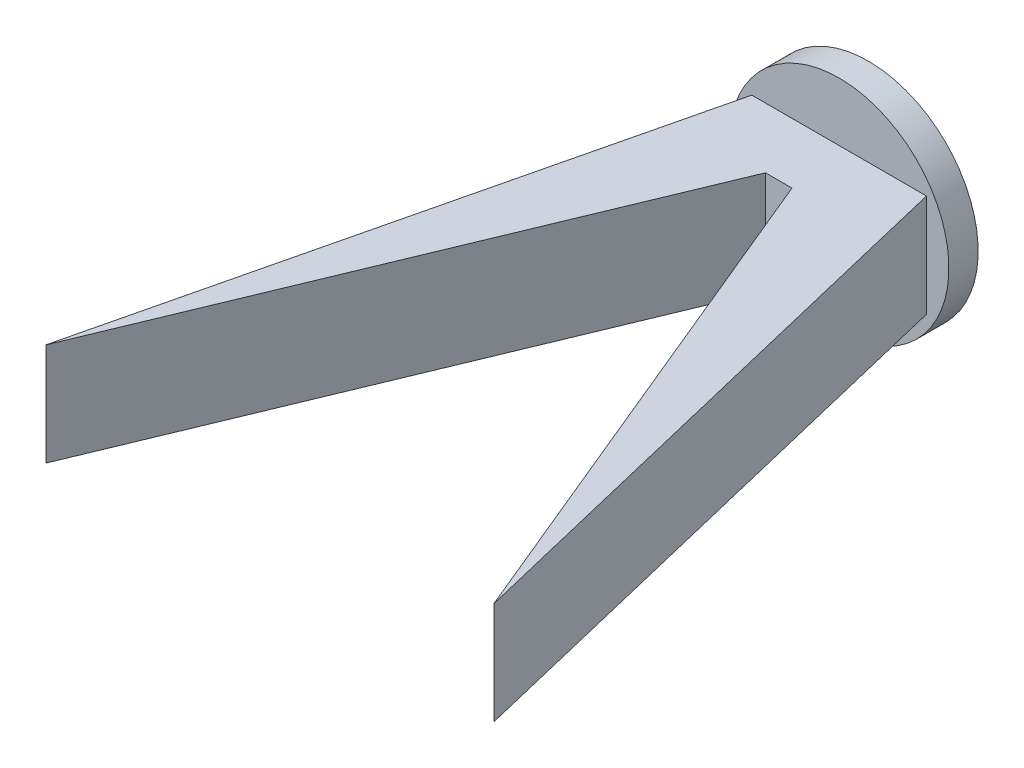
SolidWorks part; units mm, degrees
ref_plane "Front Plane" through (0, 0, 0) normal (0, 0, 1) x (1, 0, 0)
ref_plane "Top Plane" through (0, 0, 0) normal (0, 1, 0) x (1, 0, 0)
ref_plane "Right Plane" through (0, 0, 0) normal (1, 0, 0) x (0, 0, -1)
sketch "Sketch1" plane through (0, 0, 0) normal (0, 1, 0) x (1, 0, 0)
  line L0 (0, 0) -> (0, -40) construction
  line L3 (-15.3073, -36.9552) -> (-5.9695, 1.9396)
  line L4 (15.3073, -36.9552) -> (5.9695, 1.9396)
  line L5 (-0.9065, -2.1884) -> (0.9065, -2.1884)
  line L7 (-0.9065, -2.1884) -> (-15.3073, -36.9552)
  line L8 (0.9065, -2.1884) -> (15.3073, -36.9552)
  line L9 (5.9695, 1.9396) -> (-5.9695, 1.9396)
  dimension "D3" = 40
  dimension "D4" = 40
  dimension "D6" = 40
  dimension "D9" = 40
extrude "Boss-Extrude1" add sketch "Sketch1" along normal blind 7
sketch "Sketch2" plane through (0, 0, -1.9396) normal (0, 0, -1) x (-1, 0, 0)
  line L0 (-5.9695, 0) -> (5.9695, 7) construction
  line L1 (-5.9695, 7) -> (5.9695, 0) construction
  circle A0 centre (0, 3.5) radius 7.5
  dimension "D1" = 15
extrude "Boss-Extrude2" add sketch "Sketch2" along normal blind 2
